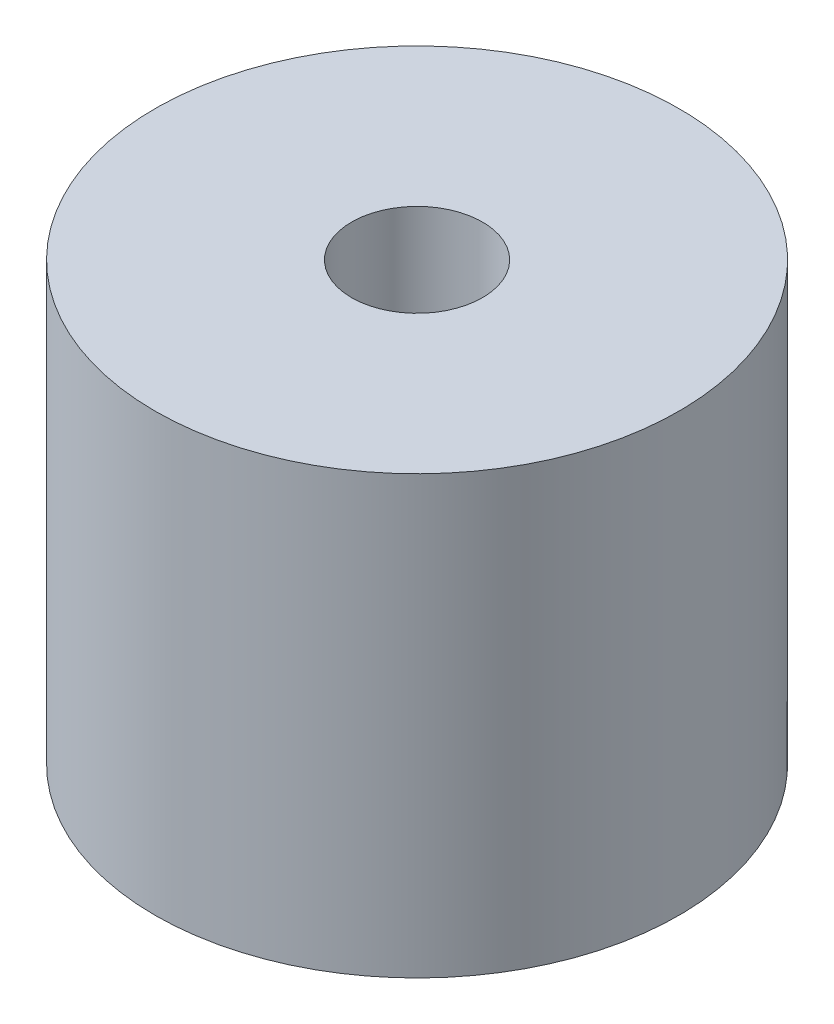
SolidWorks part; units mm, degrees
ref_plane "Front Plane" through (0, 0, 0) normal (0, 0, 1) x (1, 0, 0)
ref_plane "Top Plane" through (0, 0, 0) normal (0, 1, 0) x (1, 0, 0)
ref_plane "Right Plane" through (0, 0, 0) normal (1, 0, 0) x (0, 0, -1)
sketch "Sketch1" plane through (0, 0, 0) normal (0, 1, 0) x (1, 0, 0)
  circle A0 centre (0, 0) radius 3
  dimension "D1" = 6
extrude "Boss-Extrude1" add sketch "Sketch1" along normal blind 5
sketch "Sketch2" plane through (0, 5, 0) normal (0, 1, 0) x (1, 0, 0)
  circle A0 centre (0, 0) radius 0.75
  dimension "D1" = 1.5
extrude "Cut-Extrude1" cut sketch "Sketch2" against normal through all
